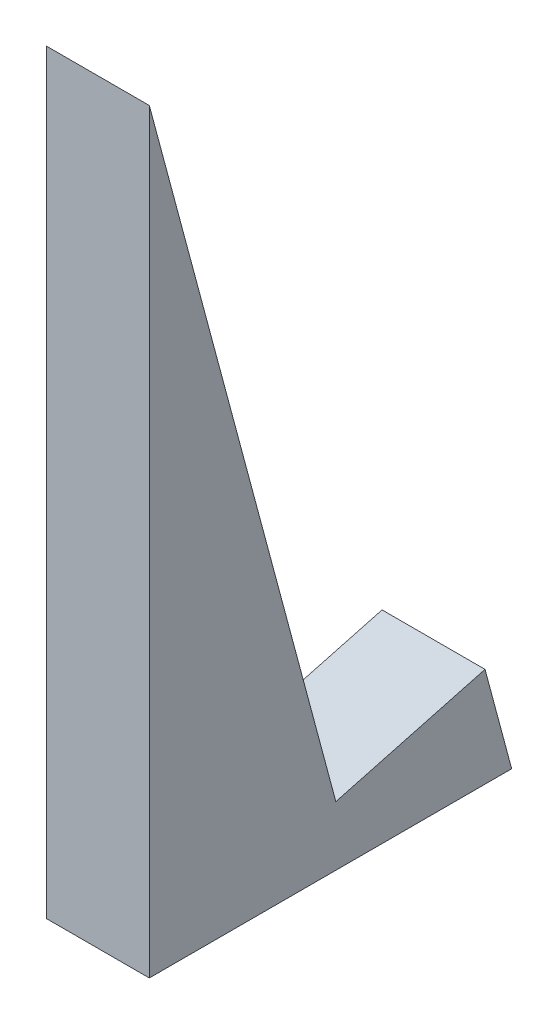
SolidWorks part; units mm, degrees
ref_plane "Plan de face" through (0, 0, 0) normal (0, 0, 1) x (1, 0, 0)
ref_plane "Plan de dessus" through (0, 0, 0) normal (0, 1, 0) x (1, 0, 0)
ref_plane "Plan de droite" through (0, 0, 0) normal (1, 0, 0) x (0, 0, -1)
sketch "Esquisse1" plane through (0, 0, 0) normal (1, 0, 0) x (0, 0, -1)
  line L0 (0, 0) -> (35.1944, 0)
  line L1 (35.1944, 0) -> (32.6062, 9.6593)
  line L2 (32.6062, 9.6593) -> (18.1173, 5.777)
  line L3 (18.1173, 5.777) -> (0, 73.3918)
  line L4 (0, 73.3918) -> (0, 0)
  line L6 (18.1173, 5.777) -> (18.1173, -6.3408) construction
  line L7 (32.6062, 9.6593) -> (32.6062, 0) construction
  point P3 (18.1173, 0)
  point P7 (18.1173, 0)
  point P9 (0, 0)
  dimension "D1" = 75
  dimension "D2" = 10
  dimension "D3" = 15
  dimension "D4" = 70
extrude "Boss.-Extru.1" add sketch "Esquisse1" along normal blind 10
